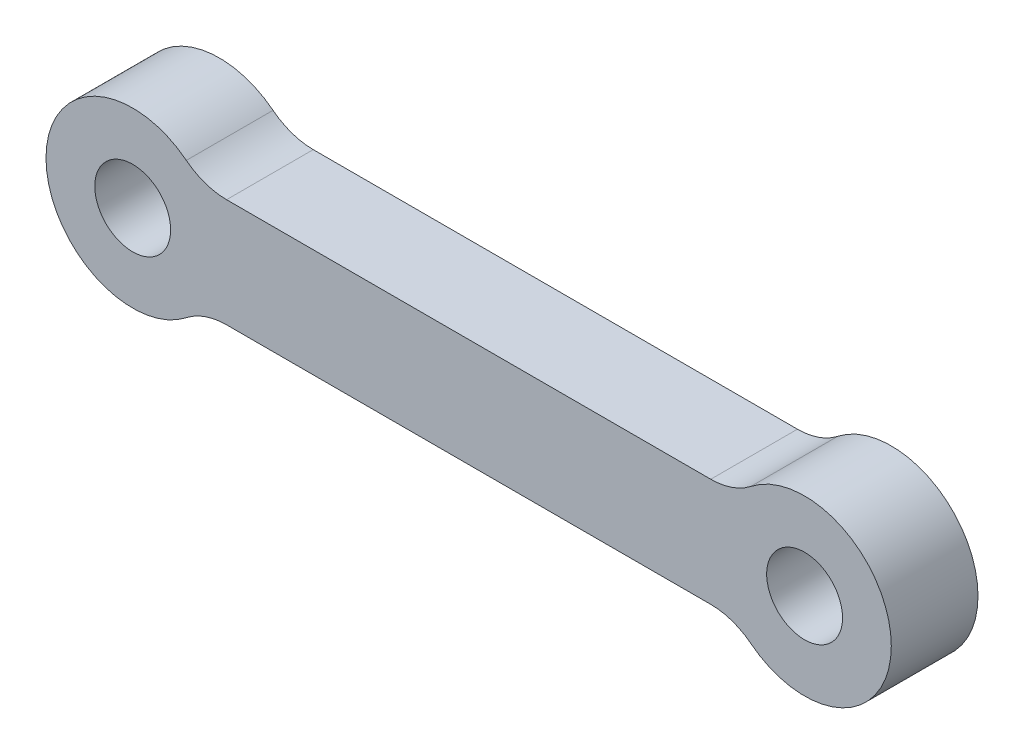
SolidWorks part; units mm, degrees
ref_plane "Front Plane" through (0, 0, 0) normal (0, 0, 1) x (1, 0, 0)
ref_plane "Top Plane" through (0, 0, 0) normal (0, 1, 0) x (1, 0, 0)
ref_plane "Right Plane" through (0, 0, 0) normal (1, 0, 0) x (0, 0, -1)
sketch "Sketch1" plane through (0, 0, 0) normal (0, 0, 1) x (1, 0, 0)
  line L0 (-15.5, 0) -> (15.5, 0) construction
  line L1 (0, 0) -> (0, 5.5911) construction
  line L2 (-12.3775, -2.5) -> (12.3775, -2.5)
  line L3 (-12.3775, 2.5) -> (12.3775, 2.5)
  circle A0 centre (-15.5, 0) radius 1.75
  circle A1 centre (-15.5, 0) radius 4
  circle A2 centre (15.5, 0) radius 4
  circle A3 centre (15.5, 0) radius 1.75
  point P4 (0, 0)
  dimension "D2" = 8
  dimension "D3" = 3.5
  dimension "D1" = 31
  dimension "D4" = 2.5
extrude "Boss-Extrude1" add sketch "Sketch1" along normal mid plane 4 contours L2 A2 L3 A1 | A1 A0 | A2 A3
fillet "Fillet1" radius 3 4 edges at (12.3775, -2.5, 0) (12.3775, 2.5, 0) (-12.3775, -2.5, 0) (-12.3775, 2.5, 0)
